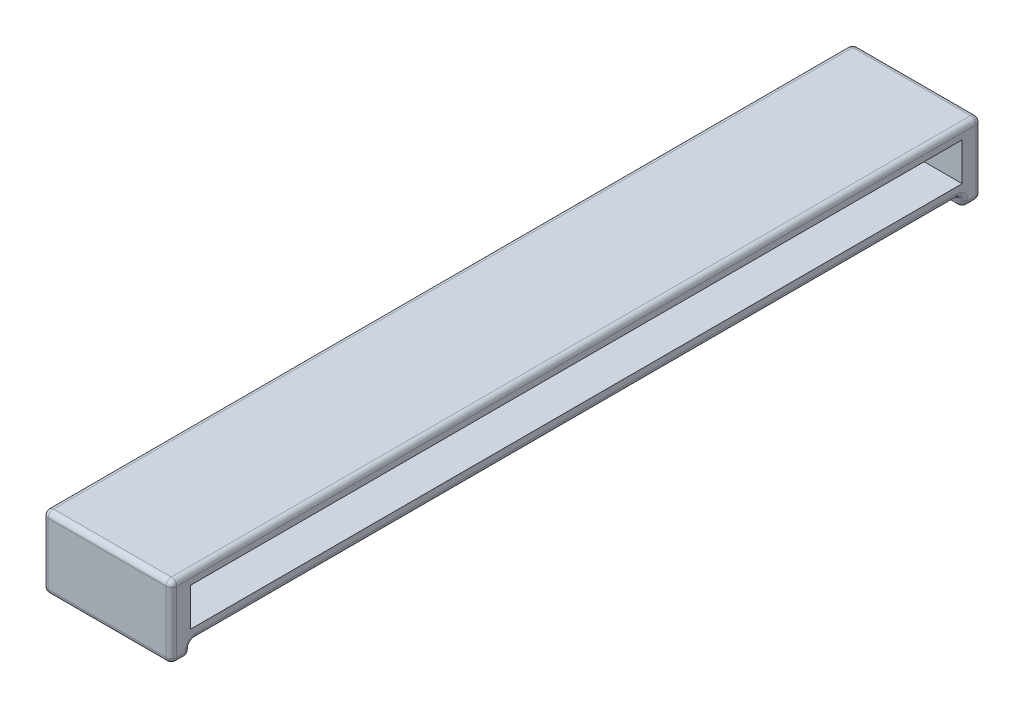
SolidWorks part; units mm, degrees
ref_plane "Front Plane" through (0, 0, 0) normal (0, 0, 1) x (1, 0, 0)
ref_plane "Top Plane" through (0, 0, 0) normal (0, 1, 0) x (1, 0, 0)
ref_plane "Right Plane" through (0, 0, 0) normal (1, 0, 0) x (0, 0, -1)
sketch "Sketch1" plane through (0, 0, 0) normal (0, 1, 0) x (1, 0, 0)
  line L0 (-17.6031, -25.4) -> (-9.1435, -25.4) construction
  line L1 (-17.6031, -25.4) -> (-17.6031, 25.4)
  line L2 (-17.6031, 25.4) -> (-9.1435, 25.4) construction
  line L3 (-9.1435, -25.4) -> (-9.1435, 25.4)
  line L4 (-17.6031, -25.4) -> (-9.1435, 25.4) construction
  line L5 (-17.6031, 25.4) -> (-9.1435, -25.4) construction
  line L6 (-1.375, 0) -> (1.375, 0) construction
  line L7 (-17.6031, -25.4) -> (-9.1435, -25.4) construction
  line L8 (-17.6031, -25.4) -> (-17.6031, -26.65)
  line L9 (-17.6031, -26.65) -> (-9.1435, -26.65)
  line L10 (-9.1435, -25.4) -> (-9.1435, -26.65)
  line L11 (-17.6031, -25.4) -> (-9.1435, -26.65) construction
  line L12 (-17.6031, -26.65) -> (-9.1435, -25.4) construction
  line L13 (-17.6031, 25.4) -> (-9.1435, 26.65) construction
  line L14 (-17.6031, 26.65) -> (-9.1435, 25.4) construction
  line L15 (-9.1435, 25.4) -> (-9.1435, 26.65)
  line L16 (-17.6031, 26.65) -> (-9.1435, 26.65)
  line L17 (-17.6031, 25.4) -> (-17.6031, 26.65)
  point P4 (-13.3733, 0)
  point P7 (-13.3733, -26.025)
  dimension "D1" = 8.4596
  dimension "D2" = 50.8
  dimension "D3" = 1.25
extrude "Boss-Extrude1" add sketch "Sketch1" along normal blind 0.75
sketch "Sketch2" plane through (0, 0, 0) normal (0, -1, 0) x (1, 0, 0)
  line L0 (-17.6031, -25.4) -> (-9.1435, -26.65) construction
  line L1 (-17.6031, 25.4) -> (-9.1435, 25.4)
  line L2 (-17.6031, 25.4) -> (-17.6031, 26.65)
  line L3 (-17.6031, 26.65) -> (-9.1435, 26.65)
  line L4 (-9.1435, 25.4) -> (-9.1435, 26.65)
  line L5 (-17.6031, 25.4) -> (-9.1435, 26.65) construction
  line L6 (-17.6031, 26.65) -> (-9.1435, 25.4) construction
  line L7 (-17.6031, -25.4) -> (-9.1435, -25.4)
  line L8 (-17.6031, -25.4) -> (-17.6031, -26.65)
  line L9 (-17.6031, -26.65) -> (-9.1435, -26.65)
  line L10 (-9.1435, -25.4) -> (-9.1435, -26.65)
  line L11 (-17.6031, -25.4) -> (-9.1435, -26.65) construction
  line L12 (-17.6031, -26.65) -> (-9.1435, -25.4) construction
  point P0 (-13.3733, 26.025)
  point P7 (-13.3733, -26.025)
extrude "Boss-Extrude2" add sketch "Sketch2" along normal blind 0.75
sketch "Sketch3" plane through (0, 0, 0) normal (0, -1, 0) x (1, 0, 0)
  line L0 (-17.6031, 25.4) -> (-17.6031, -25.4) construction
  line L1 (-17.6031, -24.3) -> (-12.1031, -24.3)
  line L2 (-17.6031, -24.3) -> (-17.6031, -21.3)
  line L3 (-17.6031, -21.3) -> (-12.1031, -21.3)
  line L4 (-12.1031, -24.3) -> (-12.1031, -21.3) construction
  line L5 (-17.6031, -24.3) -> (-12.1031, -21.3) construction
  line L6 (-17.6031, -21.3) -> (-12.1031, -24.3) construction
  line L7 (-17.6031, -25.4) -> (-9.1435, -25.4) construction
  arc A0 (-12.1031, -24.3) -> (-12.1031, -21.3) centre (-12.1031, -22.8) ccw
  point P4 (-14.8531, -22.8)
  dimension "D1" = 1.1
  dimension "D2" = 3
  dimension "D3" = 5.5
extrude "Boss-Extrude3" add sketch "Sketch3" along normal blind 1.25
pattern_linear "LPattern1" count 10 spacing 5.068 along (0, 0, 1) of "Boss-Extrude3"
sketch "Sketch4" plane through (0, 0.75, 0) normal (0, 1, 0) x (1, 0, 0)
  line L0 (-17.6031, -25.4) -> (-17.6031, 25.4)
  line L1 (-17.6031, 26.65) -> (-9.1435, 26.65)
  line L2 (-17.6031, 26.65) -> (-17.6031, 25.4)
  line L3 (-16.3531, 25.4) -> (-9.1435, 25.4)
  line L4 (-9.1435, 26.65) -> (-9.1435, 25.4)
  line L5 (-17.6031, 26.65) -> (-9.1435, 25.4) construction
  line L6 (-17.6031, 25.4) -> (-9.1435, 26.65) construction
  line L7 (-17.6031, -26.65) -> (-9.1435, -26.65)
  line L8 (-17.6031, -26.65) -> (-17.6031, -25.4)
  line L9 (-16.3531, -25.4) -> (-9.1435, -25.4)
  line L10 (-9.1435, -26.65) -> (-9.1435, -25.4)
  line L11 (-17.6031, -26.65) -> (-9.1435, -25.4) construction
  line L12 (-17.6031, -25.4) -> (-9.1435, -26.65) construction
  line L13 (-16.3531, -25.4) -> (-16.3531, 25.4)
  line L14 (-17.6031, -25.4) -> (-16.3531, -25.4) construction
  line L15 (-17.6031, 25.4) -> (-16.3531, 25.4) construction
  point P4 (-13.3733, 26.025)
  point P11 (-13.3733, -26.025)
extrude "Boss-Extrude4" add sketch "Sketch4" along normal blind 2.5
sketch "Sketch5" plane through (0, 3.25, 0) normal (0, 1, 0) x (1, 0, 0)
  line L1 (-17.6031, 26.65) -> (-9.1435, 26.65)
  line L2 (-17.6031, 26.65) -> (-17.6031, -26.65)
  line L3 (-17.6031, -26.65) -> (-9.1435, -26.65)
  line L4 (-9.1435, 26.65) -> (-9.1435, -26.65)
  line L5 (-17.6031, 26.65) -> (-9.1435, -26.65) construction
  line L6 (-17.6031, -26.65) -> (-9.1435, 26.65) construction
  point P4 (-13.3733, 0)
extrude "Boss-Extrude5" add sketch "Sketch5" along normal blind 0.75
fillet "Fillet1" radius 0.35 124 edges at (-17.6031, -0.625, 24.312) (-17.6031, -0.375, 25.4) (-9.1435, -0.375, 25.4) (-9.1435, -0.375, -25.4) (-17.6031, -0.375, -25.4) (-17.6031, -0.625, -24.3) (-17.6031, -0.625, -21.3) (-17.6031, -0.625, -19.232) (-17.6031, -0.625, -16.232) (-17.6031, -0.625, -14.164) (-17.6031, -0.625, -11.164) (-17.6031, -0.625, -9.096) (-17.6031, -0.625, -6.096) (-17.6031, -0.625, -4.028) (-17.6031, -0.625, -1.028) (-17.6031, -0.625, 1.04) (-17.6031, -0.625, 4.04) (-17.6031, -0.625, 6.108) (-17.6031, -0.625, 9.108) (-17.6031, -0.625, 11.176) (-17.6031, -0.625, 14.176) (-17.6031, -0.625, 16.244) (-17.6031, -0.625, 19.244) (-17.6031, -0.625, 21.312) (-14.8531, -1.25, -24.3) (-14.8531, -1.25, -21.3) (-13.3733, -0.75, 25.4) (-17.6031, -0.75, 26.025) (-13.3733, -0.75, 26.65) (-9.1435, -0.75, 26.025) (-14.8531, -1.25, -16.232) (-10.6031, -1.25, -17.732) (-14.8531, -1.25, -19.232) (-17.6031, -1.25, -17.732) (-10.6031, 0, 22.812) (-14.8531, 0, 24.312) (-17.6031, 0, 24.856) (-13.3733, 0, 25.4) (-9.1435, 0, 0) (-13.3733, 0, -25.4) (-17.6031, 0, -24.85) (-14.8531, 0, -24.3) (-10.6031, 0, -22.8) (-14.8531, 0, -21.3) (-17.6031, 0, -20.266) (-14.8531, 0, -19.232) (-10.6031, 0, -17.732) (-14.8531, 0, -16.232) (-17.6031, 0, -15.198) (-14.8531, 0, -14.164) (-10.6031, 0, -12.664) (-14.8531, 0, -11.164) (-17.6031, 0, -10.13) (-14.8531, 0, -9.096) (-10.6031, 0, -7.596) (-14.8531, 0, -6.096) (-17.6031, 0, -5.062) (-14.8531, 0, -4.028) (-10.6031, 0, -2.528) (-14.8531, 0, -1.028) (-17.6031, 0, 0.006) (-14.8531, 0, 1.04) (-10.6031, 0, 2.54) (-14.8531, 0, 4.04) (-17.6031, 0, 5.074) (-14.8531, 0, 6.108) (-10.6031, 0, 7.608) (-14.8531, 0, 9.108) (-17.6031, 0, 10.142) (-14.8531, 0, 11.176) (-10.6031, 0, 12.676) (-14.8531, 0, 14.176) (-17.6031, 0, 15.21) (-14.8531, 0, 16.244) (-10.6031, 0, 17.744) (-14.8531, 0, 19.244) (-17.6031, 0, 20.278) (-14.8531, 0, 21.312) (-14.8531, -1.25, 19.244) (-10.6031, -1.25, 17.744) (-14.8531, -1.25, 16.244) (-17.6031, -1.25, 17.744) (-14.8531, -1.25, 24.312) (-10.6031, -1.25, 22.812) (-14.8531, -1.25, 21.312) (-17.6031, -1.25, 22.812) (-13.3733, -0.75, -26.65) (-17.6031, -0.75, -26.025) (-13.3733, -0.75, -25.4) (-9.1435, -0.75, -26.025) (-14.8531, -1.25, -11.164) (-10.6031, -1.25, -12.664) (-14.8531, -1.25, -14.164) (-17.6031, -1.25, -12.664) (-14.8531, -1.25, -6.096) (-10.6031, -1.25, -7.596) (-14.8531, -1.25, -9.096) (-17.6031, -1.25, -7.596) (-14.8531, -1.25, -1.028) (-10.6031, -1.25, -2.528) (-14.8531, -1.25, -4.028) (-17.6031, -1.25, -2.528) (-14.8531, -1.25, 4.04) (-10.6031, -1.25, 2.54) (-14.8531, -1.25, 1.04) (-17.6031, -1.25, 2.54) (-14.8531, -1.25, 9.108) (-10.6031, -1.25, 7.608) (-14.8531, -1.25, 6.108) (-17.6031, -1.25, 7.608) (-14.8531, -1.25, 14.176) (-10.6031, -1.25, 12.676) (-14.8531, -1.25, 11.176) (-17.6031, -1.25, 12.676) (-17.6031, 1.625, -26.65) (-9.1435, 1.625, -26.65) (-17.6031, 1.625, 26.65) (-9.1435, 1.625, 26.65) (-17.6031, -1.25, -22.8) (-10.6031, -1.25, -22.8) (-13.3733, 4, -26.65) (-9.1435, 4, 0) (-13.3733, 4, 26.65) (-17.6031, 4, 0)
